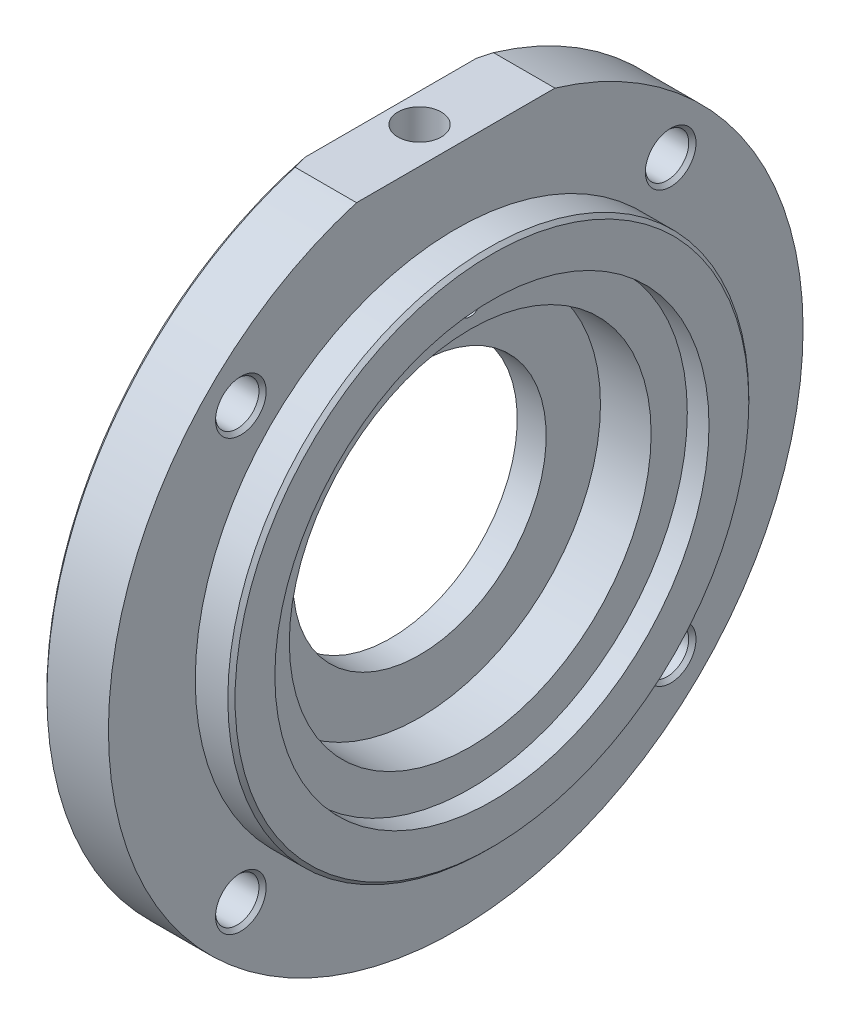
SolidWorks part; units mm, degrees
ref_plane "Front Plane" through (0, 0, 0) normal (0, 0, 1) x (1, 0, 0)
ref_plane "Top Plane" through (0, 0, 0) normal (0, 1, 0) x (1, 0, 0)
ref_plane "Right Plane" through (0, 0, 0) normal (1, 0, 0) x (0, 0, -1)
sketch "Sketch1" plane through (0, 0, 0) normal (0, 0, 1) x (1, 0, 0)
  line L0 (-4, -48) -> (-4, -17.5)
  line L1 (-4, -17.5) -> (0, -17.5)
  line L2 (0, -17.5) -> (0, -25)
  line L3 (0, -25) -> (7, -25)
  line L4 (7, -25) -> (7, -30)
  line L5 (7, -30) -> (10, -30)
  line L6 (10, -30) -> (10, -36)
  line L7 (10, -36) -> (5, -36)
  line L8 (5, -36) -> (5, -48)
  line L9 (5, -48) -> (-4, -48)
  line L10 (-17.2837, 0) -> (17.2837, 0) construction
  point P14 (0, 0)
  dimension "D1" = 35
  dimension "D2" = 50
  dimension "D3" = 96
  dimension "D4" = 72
  dimension "D5" = 60
  dimension "D6" = 14
  dimension "D7" = 10
  dimension "D8" = 2
  dimension "D9" = 5
revolve "Revolve1" add sketch "Sketch1" angle 360 about L10
chamfer "Chamfer1" distance 0.5 angle 45 1 edges at (-4, 0, 48)
chamfer "Chamfer2" distance 0.5 angle 45 1 edges at (10, 0, 36)
sketch "Sketch2" plane through (0, 0, 0) normal (1, 0, 0) x (0, 0, -1)
  line L1 (-26.7488, 83.6463) -> (26.7488, 83.6463)
  line L2 (-26.7488, 83.6463) -> (-26.7488, 46)
  line L3 (-26.7488, 46) -> (26.7488, 46)
  line L4 (26.7488, 83.6463) -> (26.7488, 46)
  line L5 (-26.7488, 83.6463) -> (26.7488, 46) construction
  line L6 (-26.7488, 46) -> (26.7488, 83.6463) construction
  point P0 (0, 64.8232)
  dimension "D1" = 46
extrude "Cut-Extrude1" cut sketch "Sketch2" against normal through all both and the other way through all
sketch "Sketch6" plane through (0, 46, 0) normal (0, 1, 0) x (1, 0, 0)
  circle A0 centre (0, 0) radius 3
  point P0 (0, 0)
  dimension "D1" = 6
extrude "Cut-Extrude2" cut sketch "Sketch6" against normal blind 7 and the other way through all
sketch "Sketch8" plane through (0, 39, 0) normal (0, 1, 0) x (1, 0, 0)
  point P0 (0, 0)
hole_wizard "Ø3.0mm Dowel Hole1" positions "Sketch8" profile "Sketch9" hole size "Ø3.0" standard "ANSI Metric"
sketch "Sketch9" plane through (0, 39, 0) normal (1, 0, 0) x (0, 0, 1)
  line L0 (0, 0) -> (0, 12.9013)
  line L1 (0, 12.9013) -> (1.5, 12)
  line L2 (1.5, 12) -> (1.5, 0)
  line L5 (1.5, 0) -> (0, 0)
  line L10 (0, 12.9013) -> (-1.5, 12) construction
  line L11 (0, -6.35) -> (0, 107.95) construction
  dimension "Hole Dia." = 3
  dimension "Hole Depth" = 12
  dimension "Drill Angle" = 118
sketch "Sketch10" plane through (10, 0, 0) normal (1, 0, 0) x (0, 0, -1)
  line L0 (-13.7113, 46) -> (13.7113, 46) construction
  point P0 (0, 28)
  dimension "D1" = 18
hole_wizard "Ø3.0mm Dowel Hole2" positions "Sketch10" profile "Sketch11" hole size "Ø3.0" standard "ANSI Metric"
sketch "Sketch11" plane through (10, 28, 0) normal (0, 1, 0) x (0, 0, -1)
  line L0 (0, 0) -> (0, 10.9013)
  line L1 (0, 10.9013) -> (1.5, 10)
  line L2 (1.5, 10) -> (1.5, 0)
  line L5 (1.5, 0) -> (0, 0)
  line L10 (0, 10.9013) -> (-1.5, 10) construction
  line L11 (0, -6.35) -> (0, 107.95) construction
  dimension "Hole Dia." = 3
  dimension "Hole Depth" = 10
  dimension "Drill Angle" = 118
sketch "Sketch14" plane through (5, 0, 0) normal (1, 0, 0) x (0, 0, -1)
  line L0 (0, 11.9025) -> (0, -11.9025) construction
  line L1 (-29.6985, 29.6985) -> (0, 0) construction
  circle A0 centre (0, 0) radius 42 construction
  point P3 (-29.6985, 29.6985)
  point P8 (0, 0)
  dimension "D1" = 84
  dimension "D2" = 45
hole_wizard "Ø6.0mm Dowel Hole2" positions "3DSketch4" profile "Sketch15" hole size "Ø6.0" standard "ANSI Metric"
sketch3d "3DSketch4"
  point P0 (5, 29.6985, 29.6985)
sketch "Sketch15" plane through (5, 29.6985, 29.6985) normal (0, 1, 0) x (0, 0, -1)
  line L0 (0, 0) -> (0, 13.8026)
  line L1 (0, 13.8026) -> (3, 12)
  line L2 (3, 12) -> (3, 0)
  line L5 (3, 0) -> (0, 0)
  line L10 (0, 13.8026) -> (-3, 12) construction
  line L11 (0, -6.35) -> (0, 107.95) construction
  dimension "Hole Dia." = 6
  dimension "Hole Depth" = 12
  dimension "Drill Angle" = 118
chamfer "Chamfer3" distance 0.5 angle 45 1 edges at (5, 29.6985, 26.6985)
pattern_circular "CirPattern1" count 4 over 360 about axis through (0, 0, 0) along (1, 0, 0) of "Chamfer3", "Ø6.0mm Dowel Hole2"
